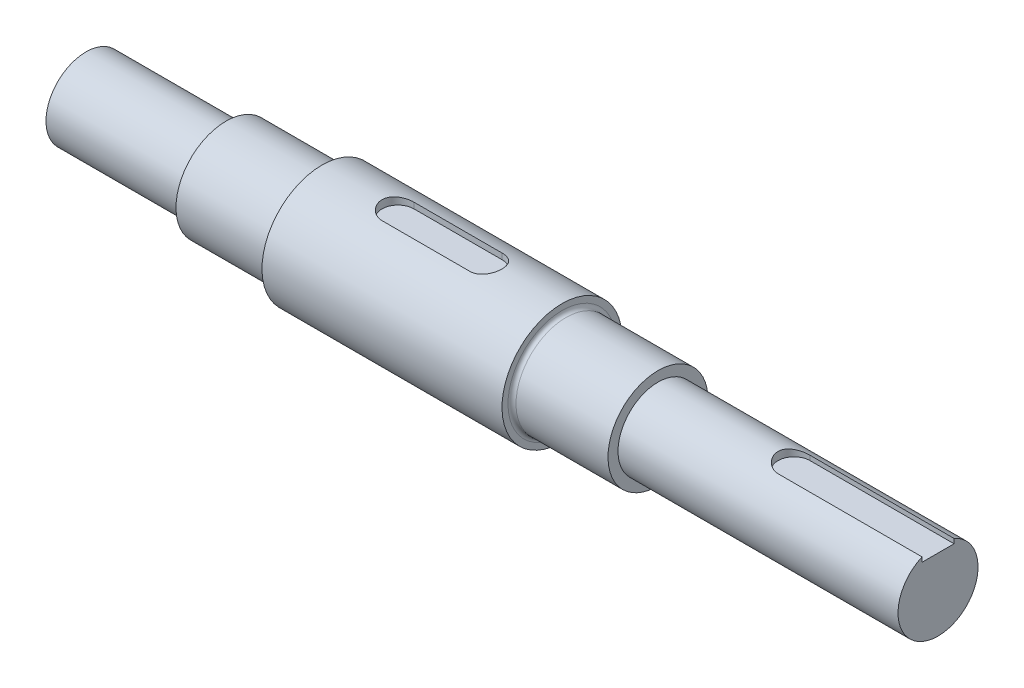
SolidWorks part; units mm, degrees
material "1.7131 (16MnCr5)"
ref_plane "Front Plane" through (0, 0, 0) normal (0, 0, 1) x (1, 0, 0)
ref_plane "Top Plane" through (0, 0, 0) normal (0, 1, 0) x (1, 0, 0)
ref_plane "Right Plane" through (0, 0, 0) normal (1, 0, 0) x (0, 0, -1)
sketch "Sketch1" plane through (0, 0, 0) normal (0, 0, 1) x (1, 0, 0)
  line L0 (-89.4367, 0) -> (89.8745, 0) construction
  line L1 (-60, 43.1339) -> (-60, -35.1585) construction
  line L3 (0, 43.1339) -> (0, -35.1585) construction
  line L4 (-54, 39.7178) -> (-54, -32.6356) construction
  line L5 (-89, 0) -> (-89, 10)
  line L6 (-89, 10) -> (-54, 10)
  line L7 (-54, 10) -> (-54, 12.5)
  line L8 (-54, 12.5) -> (-30, 12.5)
  line L9 (-30, 45.6329) -> (-30, -33.8615) construction
  line L10 (-30, 12.5) -> (-30, 15)
  line L11 (-30, 15) -> (30, 15)
  line L12 (30, 12.5) -> (30, 15)
  line L13 (54, 12.5) -> (30, 12.5)
  line L14 (54, 10) -> (54, 12.5)
  line L15 (89, 10) -> (54, 10)
  line L16 (89, 10) -> (124, 10)
  line L17 (124, 10) -> (124, 0)
  line L18 (124, 0) -> (-89, 0)
  line L19 (60, 72.6465) -> (60, -71.4395) construction
  point P20 (0, 15)
  dimension "D2" = 60
  dimension "D3" = 6
  dimension "D4" = 20
  dimension "D5" = 35
  dimension "D6" = 25
  dimension "D7" = 30
  dimension "D8" = 30
  dimension "D9" = 70
  dimension "D10" = 6
  dimension "D11" = 120
revolve "Revolve2" add sketch "Sketch1" angle 360 about L18
fillet "Fillet1" radius 1 2 edges at (30, 12.5, 0) (-30, 12.5, 0)
ref_plane "Plane1" through (0, 15, 0) normal (0, 1, 0) x (1, 0, 0)
sketch "Sketch2" plane through (0, 15, 0) normal (0, 1, 0) x (1, 0, 0)
  line L0 (11, 0) -> (-11, 0) construction
  line L5 (11, -4) -> (-11, -4)
  line L6 (11, 4) -> (-11, 4)
  arc A0 (11, -4) -> (11, 4) centre (11, 0) ccw
  arc A1 (-11, 4) -> (-11, -4) centre (-11, 0) ccw
  point P2 (0, 0)
  dimension "D1" = 30
  dimension "D2" = 8
extrude "Cut-Extrude1" cut sketch "Sketch2" against normal blind 2
ref_plane "Plane2" through (0, 10, 0) normal (0, 1, 0) x (1, 0, 0)
sketch "Sketch3" plane through (0, 10, 0) normal (0, 1, 0) x (1, 0, 0)
  line L1 (124, -4) -> (88, -4)
  line L3 (124, 4) -> (88, 4)
  line L5 (124, -10) -> (124, 10) construction
  line L7 (124, 4) -> (124, -4)
  arc A0 (88, 4) -> (88, -4) centre (88, 0) ccw
  point P3 (124, 0)
  dimension "D3" = 8
  dimension "D4" = 40
  dimension "D2" = 8
extrude "Cut-Extrude2" cut sketch "Sketch3" against normal blind 2
